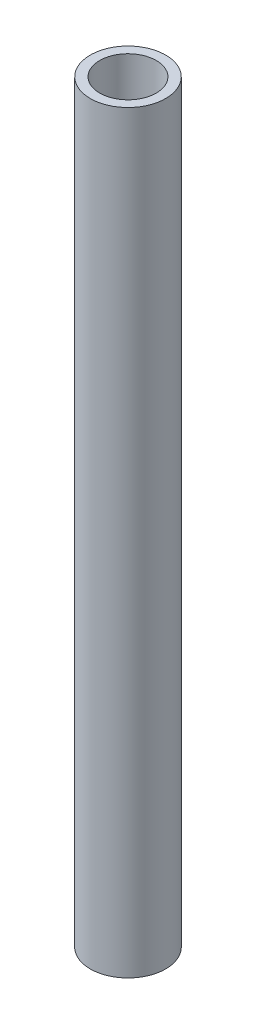
SolidWorks part; units mm, degrees
ref_plane "Plan de face" through (0, 0, 0) normal (0, 0, 1) x (1, 0, 0)
ref_plane "Plan de dessus" through (0, 0, 0) normal (0, 1, 0) x (1, 0, 0)
ref_plane "Plan de droite" through (0, 0, 0) normal (1, 0, 0) x (0, 0, -1)
sketch "Esquisse1" plane through (0, 0, 0) normal (0, 1, 0) x (1, 0, 0)
  circle A0 centre (0, 0) radius 2
  circle A1 centre (0, 0) radius 1.5
  dimension "D1" = 4
  dimension "D2" = 3
extrude "Boss.-Extru.1" add sketch "Esquisse1" along normal blind 40 contours A1
